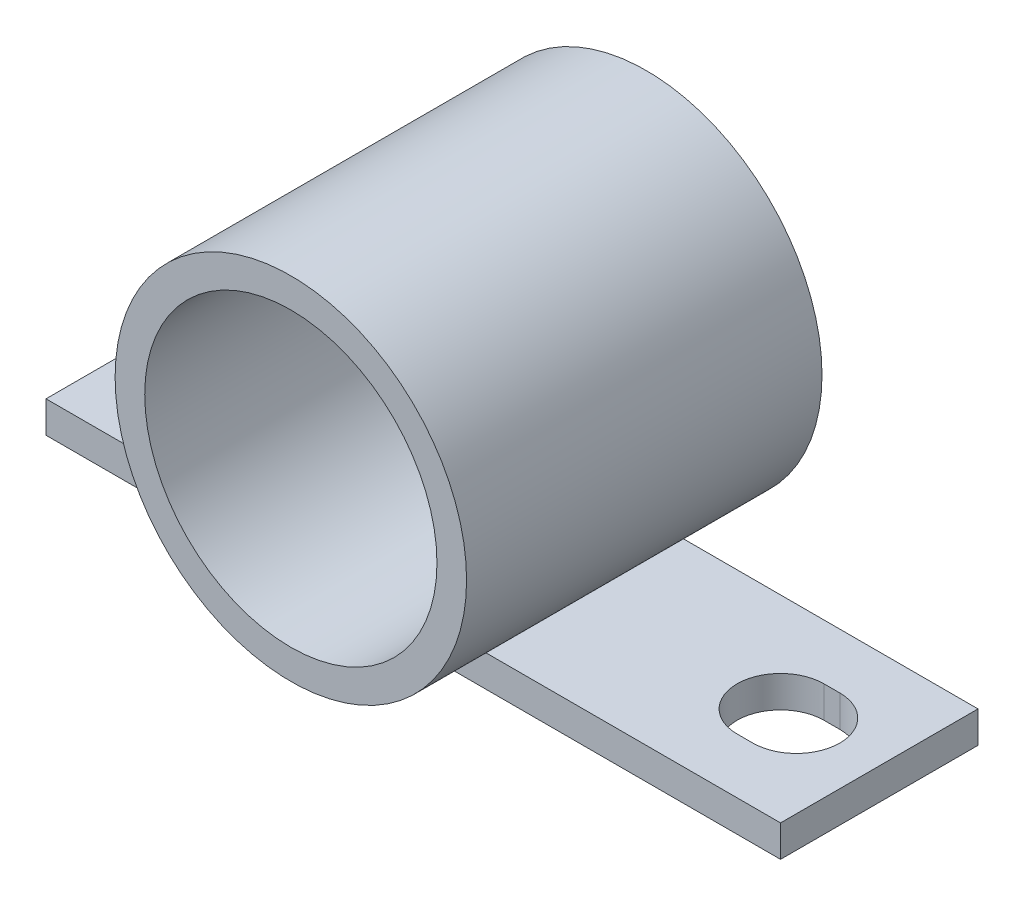
SolidWorks part; units mm, degrees
ref_plane "Спереди" through (0, 0, 0) normal (0, 0, 1) x (1, 0, 0)
ref_plane "Сверху" through (0, 0, 0) normal (0, 1, 0) x (1, 0, 0)
ref_plane "Справа" through (0, 0, 0) normal (1, 0, 0) x (0, 0, -1)
sketch "Эскиз1" plane through (0, 0, 0) normal (0, 1, 0) x (1, 0, 0)
  line L0 (0, 0) -> (0, 20.8351) construction
  line L1 (-46.5, -12.5) -> (46.5, -12.5)
  line L2 (-46.5, -12.5) -> (-46.5, 12.5)
  line L3 (-46.5, 12.5) -> (46.5, 12.5)
  line L4 (46.5, -12.5) -> (46.5, 12.5)
  line L5 (-46.5, -12.5) -> (46.5, 12.5) construction
  line L6 (-46.5, 12.5) -> (46.5, -12.5) construction
  line L7 (-36, 0) -> (-34, 0) construction
  line L8 (-36, 5.5) -> (-34, 5.5)
  line L9 (-36, -5.5) -> (-34, -5.5)
  line L10 (36, 0) -> (34, 0) construction
  line L11 (36, 5.5) -> (34, 5.5)
  line L12 (36, -5.5) -> (34, -5.5)
  arc A0 (36, 5.5) -> (36, -5.5) centre (36, 0) cw
  arc A1 (34, -5.5) -> (34, 5.5) centre (34, 0) cw
  arc A2 (-36, 5.5) -> (-36, -5.5) centre (-36, 0) ccw
  arc A3 (-34, -5.5) -> (-34, 5.5) centre (-34, 0) ccw
  point P0 (0, 0)
  point P8 (35, 0)
  point P14 (-35, 0)
  dimension "D3" = 70
  dimension "D5" = 13
  dimension "D1" = 93
  dimension "D2" = 25
  dimension "D4" = 11
extrude "Бобышка-Вытянуть1" add sketch "Эскиз1" along normal blind 4
sketch "Эскиз2" plane through (0, 0, 12.5) normal (0, 0, 1) x (1, 0, 0)
  line L0 (-46.5, 4) -> (46.5, 4) construction
  line L3 (46.5, 4) -> (46.5, 0) construction
  circle A0 centre (0, 26.25) radius 22.25
  circle A1 centre (0, 26.25) radius 18.5
  point P9 (46.5, 2)
  dimension "D1" = 44.5
  dimension "D2" = 37
  dimension "D3" = 46.5
extrude "Бобышка-Вытянуть2" add sketch "Эскиз2" along normal blind 15.5 and the other way blind 29.5 separate body
